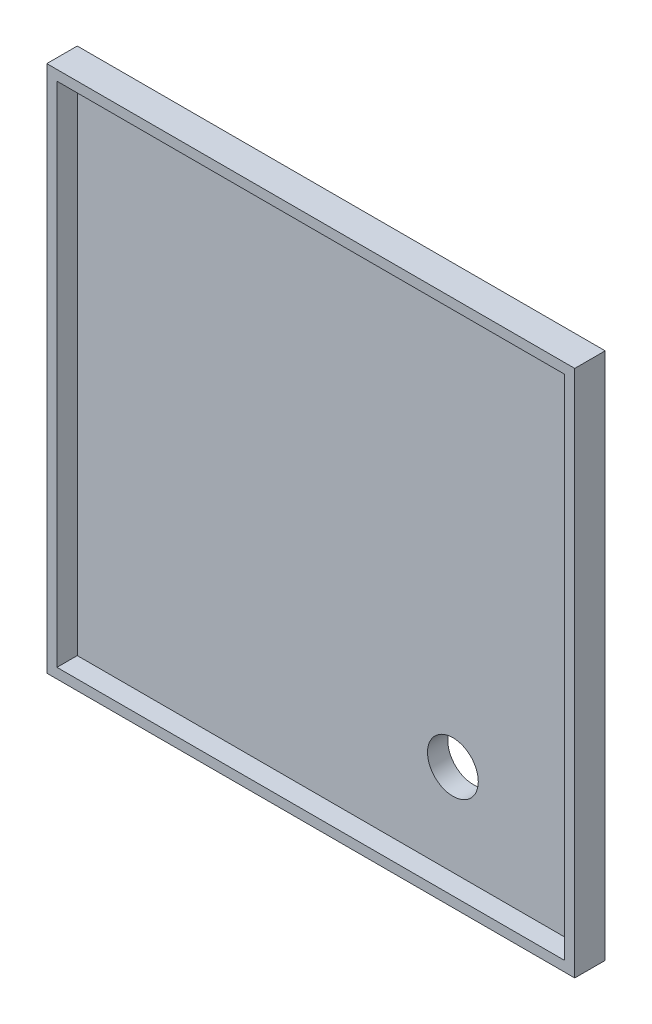
SolidWorks part; units mm, degrees
ref_plane "Plan de face" through (0, 0, 0) normal (0, 0, 1) x (1, 0, 0)
ref_plane "Plan de dessus" through (0, 0, 0) normal (0, 1, 0) x (1, 0, 0)
ref_plane "Plan de droite" through (0, 0, 0) normal (1, 0, 0) x (0, 0, -1)
sketch "Esquisse1" plane through (0, 0, 0) normal (0, 0, 1) x (1, 0, 0)
  line L1 (0, 0) -> (520, 0)
  line L2 (0, 0) -> (0, 520)
  line L3 (0, 520) -> (520, 520)
  line L4 (520, 0) -> (520, 520)
  dimension "D1" = 520
  dimension "D2" = 520
extrude "Boss.-Extru.1" add sketch "Esquisse1" along normal blind 10
sketch "Esquisse2" plane through (0, 0, 10) normal (0, 0, 1) x (1, 0, 0)
  line L0 (520, 520) -> (0, 520) construction
  line L1 (20, 500) -> (500, 500)
  line L2 (20, 500) -> (20, 20)
  line L3 (20, 20) -> (500, 20)
  line L4 (500, 500) -> (500, 20)
  line L5 (0, 520) -> (0, 0) construction
  line L6 (0, 0) -> (520, 0) construction
  line L7 (520, 0) -> (520, 520) construction
  dimension "D1" = 20
  dimension "D2" = 20
  dimension "D3" = 20
  dimension "D4" = 20
extrude "Boss.-Extru.2" add sketch "Esquisse2" along normal blind 10
sketch "Esquisse3" plane through (0, 0, 10) normal (0, 0, 1) x (1, 0, 0)
  line L1 (0, 0) -> (520, 0)
  line L2 (0, 0) -> (0, 520)
  line L3 (0, 520) -> (520, 520)
  line L4 (520, 0) -> (520, 520)
  line L5 (10, 10) -> (510, 10)
  line L6 (10, 10) -> (10, 510)
  line L7 (10, 510) -> (510, 510)
  line L8 (510, 10) -> (510, 510)
  dimension "D1" = 10
  dimension "D2" = 10
  dimension "D3" = 10
  dimension "D4" = 10
extrude "Boss.-Extru.3" add sketch "Esquisse3" along normal blind 20
sketch "Esquisse4" plane through (0, 0, 0) normal (0, 0, -1) x (-1, 0, 0)
  line L0 (0, 0) -> (-520, 0) construction
  line L1 (-520, 0) -> (-520, 520) construction
  circle A0 centre (-390, 110) radius 25
  dimension "D1" = 50
  dimension "D2" = 110
  dimension "D3" = 130
extrude "Enlèv. mat.-Extru.1" cut sketch "Esquisse4" against normal through all
